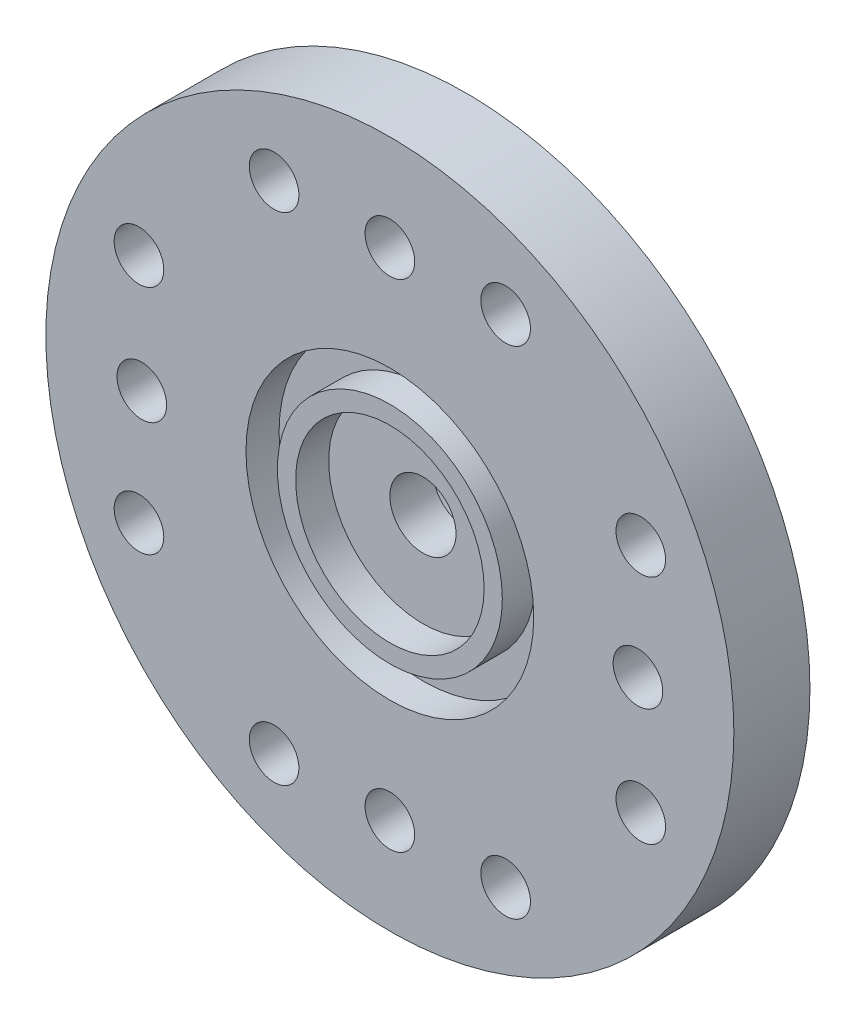
SolidWorks part; units mm, degrees
ref_plane "Front Plane" through (0, 0, 0) normal (0, 0, 1) x (1, 0, 0)
ref_plane "Top Plane" through (0, 0, 0) normal (0, 1, 0) x (1, 0, 0)
ref_plane "Right Plane" through (0, 0, 0) normal (1, 0, 0) x (0, 0, -1)
sketch "Sketch1" plane through (0, 0, 0) normal (0, 0, 1) x (1, 0, 0)
  circle A0 centre (0, 0) radius 10.4
  dimension "D1" = 20.8
extrude "Boss-Extrude1" add sketch "Sketch1" along normal blind 2.3
hole_wizard "#96 (0.0063) Diameter Hole1" positions "Sketch7" profile "Sketch8" hole size "#96" standard "ANSI Inch" end condition through all
sketch "Sketch7" plane through (0, 0, 2.3) normal (0, 0, 1) x (1, 0, 0)
  circle A0 centre (0, 0) radius 10.4
  point P0 (0, 7.5)
  point P2 (-3.5, 7.5)
  point P4 (3.5, 7.5)
  point P6 (-7.5, 0)
  point P8 (-7.5848, 3.5)
  point P10 (-7.5848, -3.5)
  dimension "D1" = 20.8
  dimension "D2" = 7.5
  dimension "D3" = 3.5
  dimension "D4" = 3.5
  dimension "D5" = 7.5
  dimension "D6" = 3.5
  dimension "D7" = 3.5
sketch "Sketch8" plane through (0, 7.5, 2.3) normal (1, 0, 0) x (0, -1, 0)
  line L0 (0, 0) -> (0, 2.3)
  line L1 (0, 2.3) -> (0.75, 2.3)
  line L2 (0.75, 2.3) -> (0.75, 0)
  line L5 (0.75, 0) -> (0, 0)
  line L11 (0, -6.35) -> (0, 107.95) construction
  dimension "Thru Hole Dia." = 1.5
  dimension "Thru Hole Depth" = 2.3
mirror "Mirror1" about plane through (0, 0, 0) normal (0, 1, 0) of "#96 (0.0063) Diameter Hole1"
mirror "Mirror2" about plane through (0, 0, 0) normal (1, 0, 0) of "#96 (0.0063) Diameter Hole1"
sketch "Sketch9" plane through (0, 0, 0) normal (0, 0, -1) x (-1, 0, 0)
  circle A0 centre (0, 0) radius 4.4
  circle A1 centre (0, 0) radius 3
  dimension "D1" = 8.8
  dimension "D2" = 6
extrude "Boss-Extrude2" add sketch "Sketch9" along normal blind 3
sketch "Sketch10" plane through (0, 0, 2.3) normal (0, 0, 1) x (1, 0, 0)
  circle A0 centre (0, 0) radius 4.35
  circle A1 centre (0, 0) radius 3.4
  dimension "D1" = 8.7
  dimension "D2" = 6.8
extrude "Cut-Extrude1" cut sketch "Sketch10" against normal blind 1
sketch "Sketch11" plane through (0, 0, 2.3) normal (0, 0, 1) x (1, 0, 0)
  circle A0 centre (0, 0) radius 2.85
  dimension "D1" = 5.7
extrude "Cut-Extrude2" cut sketch "Sketch11" against normal blind 1
sketch "Sketch12" plane through (0, 0, 1.3) normal (0, 0, 1) x (1, 0, 0)
  circle A0 centre (0, 0) radius 1
  dimension "D1" = 2
extrude "Cut-Extrude3" cut sketch "Sketch12" against normal blind 4
